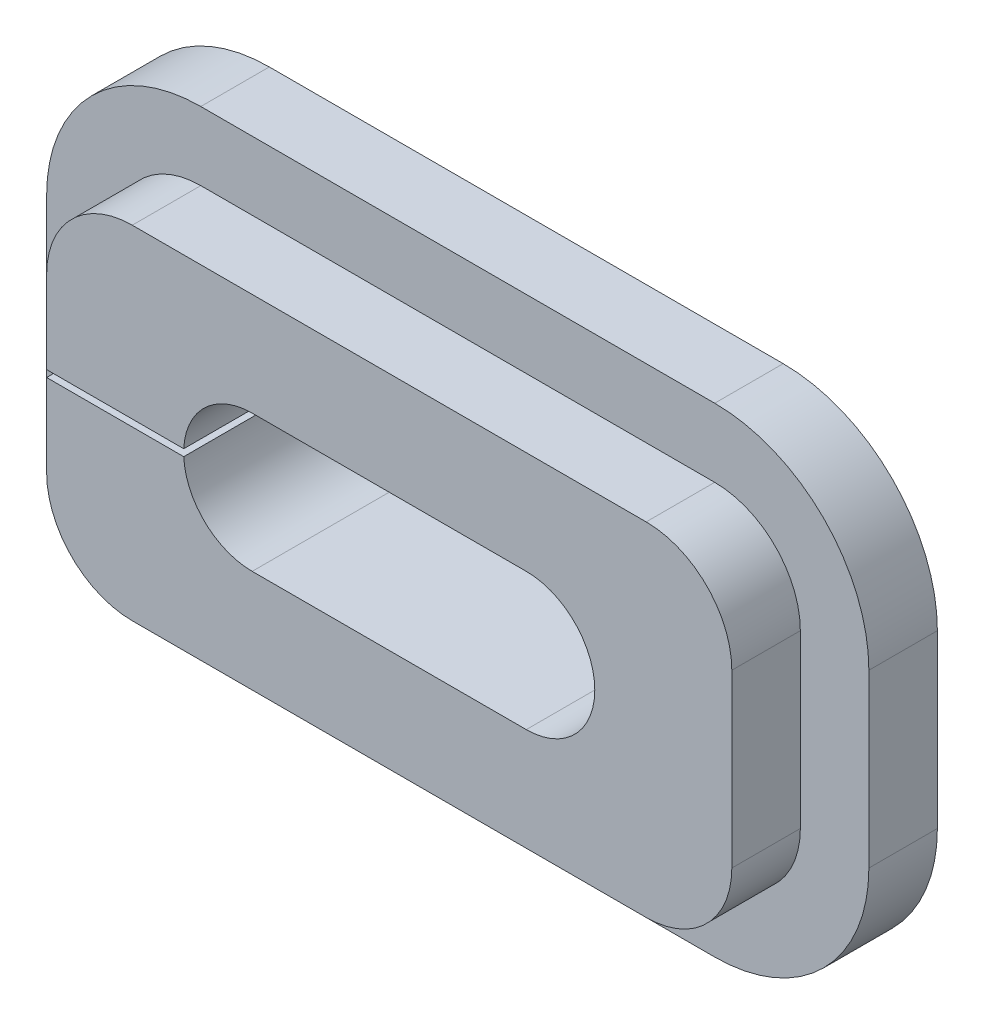
SolidWorks part; units mm, degrees
ref_plane "Front Plane" through (0, 0, 0) normal (0, 0, 1) x (1, 0, 0)
ref_plane "Top Plane" through (0, 0, 0) normal (0, 1, 0) x (1, 0, 0)
ref_plane "Right Plane" through (0, 0, 0) normal (1, 0, 0) x (0, 0, -1)
sketch "Sketch1" plane through (0, 0, 0) normal (0, 0, 1) x (1, 0, 0)
  line L0 (-10, 5) -> (10, -5) construction
  line L1 (-10, 5) -> (10, 5)
  line L2 (-10, 5) -> (-10, -5)
  line L3 (-10, -5) -> (10, -5)
  line L4 (10, 5) -> (10, -5)
  line L5 (-6, -2) -> (6, 2) construction
  line L6 (6, 2) -> (-6, 2)
  line L7 (6, 2) -> (6, -2)
  line L8 (6, -2) -> (-6, -2)
  line L9 (-6, 2) -> (-6, -2)
  line L10 (-4, 0) -> (4, 0) construction
  circle A0 centre (-4, 0) radius 2
  circle A1 centre (4, 0) radius 2
  dimension "D1" = 20
  dimension "D2" = 10
  dimension "D3" = 4
  dimension "D4" = 12
extrude "Boss-Extrude1" add sketch "Sketch1" along normal blind 2 contours L4 L1 L2 L3 L9 L6 L7 L8 | A0 L6 L9 | A0 L9 L8 | A1 L8 L7 | A1 L7 L6
fillet "Fillet1" radius 2.5 4 edges at (10, 5, 1) (10, -5, 1) (-10, -5, 1) (-10, 5, 1)
sketch "Sketch2" plane through (0, 0, 0) normal (0, 0, -1) x (-1, 0, 0)
  line L0 (-4, 2) -> (4, 2)
  line L1 (-12, 7) -> (12, 7)
  line L2 (-12, 7) -> (-12, -7)
  line L3 (-12, -7) -> (12, -7)
  line L4 (12, 7) -> (12, -7)
  line L5 (4, -2) -> (-4, -2)
  line L6 (-12, -7) -> (12, 7) construction
  line L7 (-7.5, 2.5) -> (7.5, 2.5) construction
  line L8 (7.5, 2.5) -> (7.5, -2.5) construction
  line L9 (7.5, -2.5) -> (-7.5, -2.5) construction
  line L10 (-7.5, -2.5) -> (-7.5, 2.5) construction
  arc A0 (-4, 2) -> (-4, -2) centre (-4, 0) ccw
  arc A1 (4, 2) -> (4, -2) centre (4, 0) cw
  circle A2 centre (-7.5, 2.5) radius 4.5
  arc A3 (-7.5, 5) -> (-10, 2.5) centre (-7.5, 2.5) ccw construction
  circle A4 centre (-7.5, -2.5) radius 4.5
  circle A5 centre (7.5, -2.5) radius 4.5
  circle A6 centre (7.5, 2.5) radius 4.5
  point P26 (-7.5, -0.7237)
  point P27 (6.9714, -2.5)
  arc M18 (4, 2) -> (4, -2) centre (4, 0) cw
  line M19 (4, -2) -> (-4, -2)
  arc M20 (-4, -2) -> (-4, 2) centre (-4, 0) cw
  line M21 (-4, 2) -> (4, 2)
  line M22 (7.5, 5) -> (-7.5, 5)
  arc M23 (-7.5, 5) -> (-10, 2.5) centre (-7.5, 2.5) ccw
  line M24 (-10, 2.5) -> (-10, -2.5)
  arc M25 (-10, -2.5) -> (-7.5, -5) centre (-7.5, -2.5) ccw
  line M26 (-7.5, -5) -> (7.5, -5)
  arc M27 (7.5, -5) -> (10, -2.5) centre (7.5, -2.5) ccw
  line M28 (10, -2.5) -> (10, 2.5)
  arc M29 (10, 2.5) -> (7.5, 5) centre (7.5, 2.5) ccw
  dimension "D1" = 2
extrude "Boss-Extrude2" add sketch "Sketch2" along normal blind 2 contours A6 L1 A2 M22 | A4 A2 M24 M23 M22 | A4 A2 M24 | A4 A2 L2 | A2 A4 M26 M25 M24 | A5 A4 L3 M26 | A6 A5 M28 M27 M26 | A6 A5 M28 | A6 A5 L4 | A6 A5 M22 M29 M28 | A4 A2 M20 M21 M22 M23 M24 | A0 A4 A2 M24 | A4 L5 A2 M26 M20 M24 M25 | A5 L5 A4 M26 | A6 A5 M18 M19 M26 M27 M28 | A1 A6 A5 M28 | A6 A5 M22 M21 M18 M28 M29 | A6 A2 L0 M22
sketch "Sketch3" plane through (0, 0, 0) normal (0, 0, 1) x (1, 0, 0)
  line L0 (0, 0) -> (-4, 0) construction
  line L1 (-12, 0.1) -> (-4, 0.1)
  line L2 (-12, 0.1) -> (-12, -0.1)
  line L3 (-12, -0.1) -> (-4, -0.1)
  line L4 (-4, 0.1) -> (-4, -0.1)
  line L5 (-12, 2.5) -> (-12, -2.5) construction
  line L6 (-4, 0.1) -> (-4, 2) construction
  dimension "D1" = 0.2
extrude "Cut-Extrude1" cut sketch "Sketch3" against normal through all both and the other way through all
